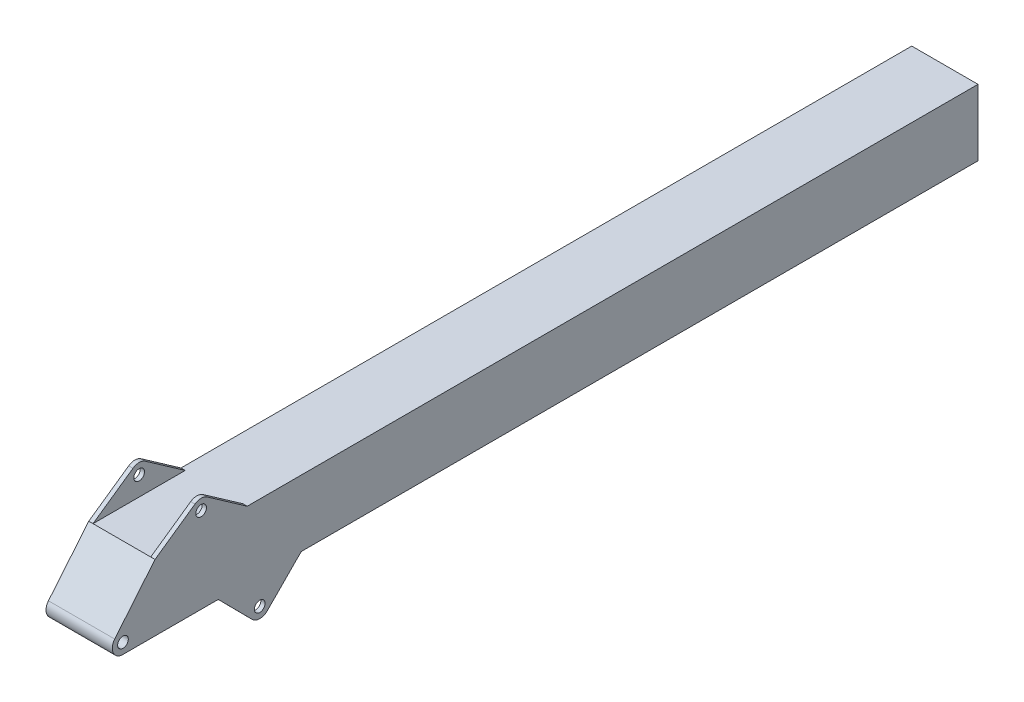
SolidWorks part; units mm, degrees
material "Plain Carbon Steel"
ref_plane "Front Plane" through (0, 0, 0) normal (0, 0, 1) x (1, 0, 0)
ref_plane "Top Plane" through (0, 0, 0) normal (0, 1, 0) x (1, 0, 0)
ref_plane "Right Plane" through (0, 0, 0) normal (1, 0, 0) x (0, 0, -1)
sketch "Sketch1" plane through (0, 0, 0) normal (1, 0, 0) x (0, 0, -1)
  line L1 (2000, 310) -> (2000, 0)
  line L3 (2000, 0) -> (-2000, 0)
  line L4 (-2038.5422, 81.8512) -> (-1850, 310)
  line L5 (-1850, 310) -> (2000, 310)
  circle A0 centre (-2000, 50) radius 25
  arc A1 (-2000, 0) -> (-2038.5422, 81.8512) centre (-2000, 50) cw
  dimension "D1" = 50
  dimension "D2" = 50
  dimension "D3" = 4000
  dimension "D4" = 310
  dimension "D5" = 3850
extrude "Boss-Extrude1" add sketch "Sketch1" against normal blind 310
shell "Shell1" thickness 20
ref_plane "Plane1" through (0, 0, 1840.5824) normal (0, 0, -1) x (1, 0, 0)
sketch "Sketch2" plane through (0, 0, 1840.5824) normal (0, 0, -1) x (1, 0, 0)
  line L0 (-20, -20) -> (-20, -290) construction
  line L1 (-290, -20) -> (-20, -20) construction
  line L2 (-290, -20) -> (-290, -290) construction
  line L3 (-290, -290) -> (-20, -290) construction
  line L4 (-20, -20) -> (-20, -290)
  line L5 (-290, -20) -> (-20, -20)
  line L6 (-290, -20) -> (-290, -290)
  line L7 (-290, -290) -> (-20, -290)
extrude "Boss-Extrude3" add sketch "Sketch2" against normal up to body separate body
sketch "Sketch3" plane through (0, 0, 0) normal (1, 0, 0) x (0, 0, -1)
  line L0 (-1553.9689, 0) -> (-1166.0311, 0)
  line L1 (-2000, 0) -> (2000, 0) construction
  line L2 (-1166.0311, 0) -> (-1324.452, -160.1616)
  line L3 (-1395.548, -160.1616) -> (-1553.9689, 0)
  line L4 (-1360, -125) -> (-1360, 0) construction
  line L5 (-1850, 310) -> (-1662.9732, 440.9576)
  line L6 (-1605.6155, 440.9576) -> (-1418.5887, 310)
  line L7 (-1634.2943, 400) -> (-1634.2943, 310) construction
  line L8 (-1850, 310) -> (-1634.2943, 310)
  line L9 (-1634.2943, 310) -> (-1418.5887, 310)
  line L10 (2000, 310) -> (-1850, 310) construction
  arc A0 (-1324.452, -160.1616) -> (-1395.548, -160.1616) centre (-1360, -125) cw
  circle A1 centre (-1360, -125) radius 25
  circle A2 centre (-2000, 50) radius 25 construction
  circle A3 centre (-2000, 50) radius 25 construction
  arc A4 (-1605.6155, 440.9576) -> (-1662.9732, 440.9576) centre (-1634.2943, 400) ccw
  circle A5 centre (-1634.2943, 400) radius 25
  dimension "D1" = 50
  dimension "D2" = 50
  dimension "D3" = 640
  dimension "D4" = 50
  dimension "D5" = 50
  dimension "D6" = 90
  dimension "D7" = 125
  dimension "D8" = 35
extrude "Boss-Extrude4" add sketch "Sketch3" against normal blind 20
ref_plane "Plane2" through (-155, 0, 0) normal (-1, 0, 0) x (0, 0, 1)
mirror "Mirror1" about plane through (-155, 0, 0) normal (-1, 0, 0) of "Boss-Extrude4"
